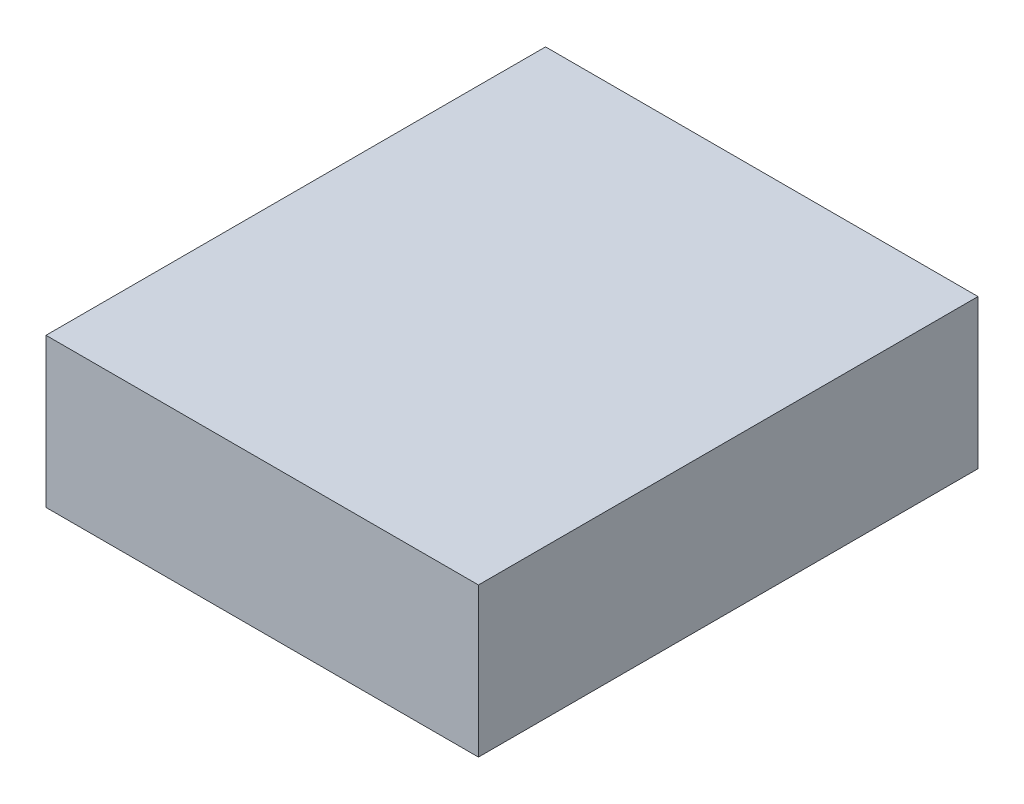
SolidWorks part; units mm, degrees
ref_plane "Front Plane" through (0, 0, 0) normal (0, 0, 1) x (1, 0, 0)
ref_plane "Top Plane" through (0, 0, 0) normal (0, 1, 0) x (1, 0, 0)
ref_plane "Right Plane" through (0, 0, 0) normal (1, 0, 0) x (0, 0, -1)
sketch "Sketch1" plane through (0, 0, 0) normal (0, 1, 0) x (1, 0, 0)
  line L1 (-119.5729, 47.125) -> (-61.5729, 47.125)
  line L2 (-119.5729, 47.125) -> (-119.5729, -19.875)
  line L3 (-119.5729, -19.875) -> (-61.5729, -19.875)
  line L4 (-61.5729, 47.125) -> (-61.5729, -19.875)
  line L5 (-119.5729, 47.125) -> (-61.5729, -19.875) construction
  line L6 (-119.5729, -19.875) -> (-61.5729, 47.125) construction
  point P0 (-90.5729, 13.625)
  dimension "D1" = 67
  dimension "D2" = 58
extrude "Boss-Extrude1" add sketch "Sketch1" along normal blind 20
